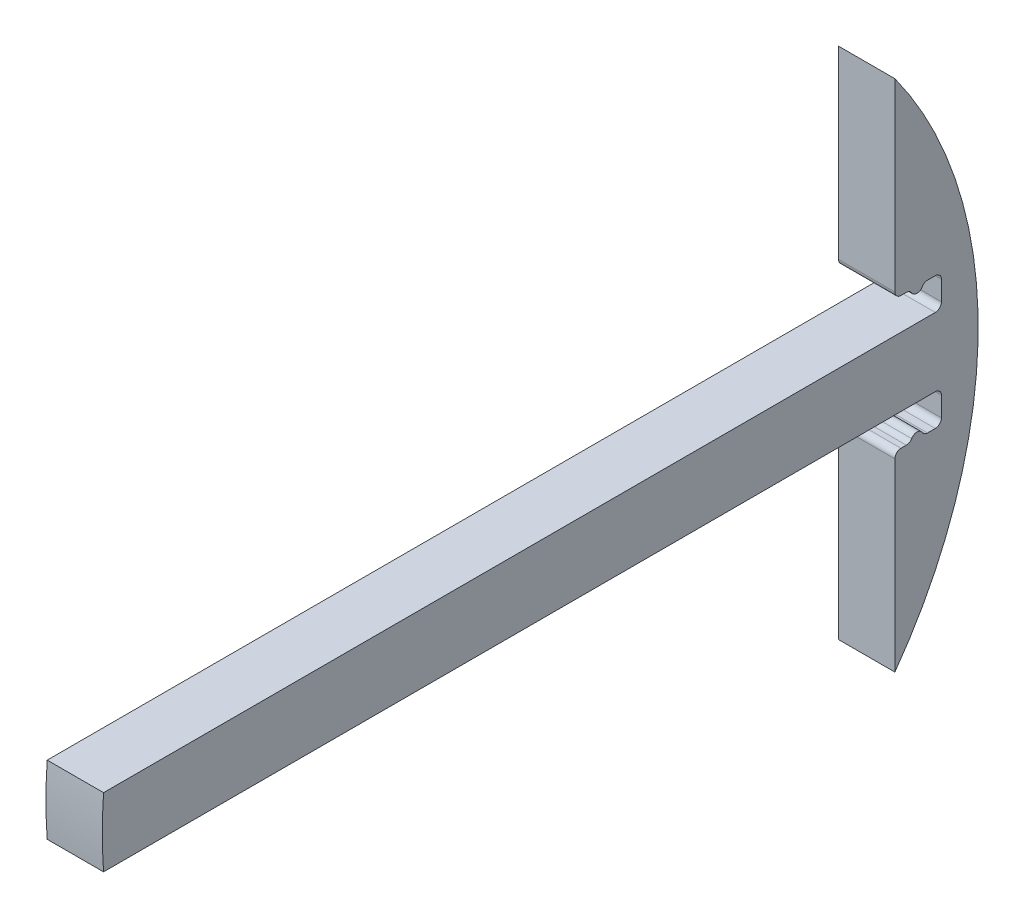
SolidWorks part; units mm, degrees
ref_plane "前视基准面" through (0, 0, 0) normal (0, 0, 1) x (1, 0, 0)
ref_plane "上视基准面" through (0, 0, 0) normal (0, 1, 0) x (1, 0, 0)
ref_plane "右视基准面" through (0, 0, 0) normal (1, 0, 0) x (0, 0, -1)
other "Configuration Table"
sketch "Sketch1" plane through (0, 0, 0) normal (1, 0, 0) x (0, 0, -1)
  circle A0 centre (0, 0) radius 35.75
  dimension "D1" = 71.5
extrude "Boss-Extrude1" add sketch "Sketch1" along normal blind 4.6
sketch "Sketch2" plane through (4.6, 0, 0) normal (1, 0, 0) x (0, 0, -1)
  line L0 (0, 0) -> (35.75, 0)
  line L1 (35.75, 0) -> (35.75, 2.8)
  line L2 (35.75, 2.8) -> (-42.7435, 2.8)
  line L3 (-42.7435, 2.8) -> (-42.7435, -2.8)
  line L4 (-42.7435, -2.8) -> (35.75, -2.8)
  line L5 (35.75, -2.8) -> (35.75, 0)
  line L6 (35.6402, 2.8) -> (32.75, 2.8)
  line L7 (32.75, 2.8) -> (32.75, 5.4)
  line L8 (32.75, 5.4) -> (28.95, 5.4)
  line L9 (28.95, 5.4) -> (28.95, 29.2614)
  line L10 (28.95, 29.2614) -> (35.6402, 29.2614)
  line L11 (35.6402, 29.2614) -> (35.75, 2.8)
  line L12 (35.75, -2.8) -> (-42.7435, -2.8)
  line L13 (32.75, -2.8) -> (32.75, -5.4)
  line L14 (32.75, -5.4) -> (28.95, -5.4)
  line L15 (35.6402, -29.2614) -> (35.75, -2.8)
  line L16 (28.95, -5.4) -> (28.95, -29.2614)
  line L17 (28.95, 5.4) -> (28.95, 2.8)
  line L18 (28.95, -5.4) -> (28.95, -2.8)
  circle A0 centre (0, 0) radius 35.75 construction
  circle A1 centre (0, 0) radius 35.75
  circle A2 centre (30.75, 5.4) radius 0.5
  circle A3 centre (30.75, -5.4) radius 0.5
  circle M6 centre (0, 0) radius 35.75
  dimension "D6" = 2
  dimension "D2" = 1
  dimension "D1" = 2.8
  dimension "D3" = 3
  dimension "D4" = 3.8
  dimension "D5" = 2.6
extrude "Cut-Extrude1" cut sketch "Sketch2" against normal through all contours L17 L9 L2 M6 | L16 L18 L4 M6 | A2 L8 L17 L2 L7 | L14 A3 L13 L12 L18
fillet "Fillet1" radius 0.5 6 edges at (2.3, -5.4, -28.95) (2.3, -2.8, -32.75) (2.3, -5.4, -32.75) (2.3, 2.8, -32.75) (2.3, 5.4, -32.75) (2.3, 5.4, -28.95)
fillet "Fillet2" radius 0.5 4 edges at (2.3, -5.4, -31.25) (2.3, -5.4, -30.25) (2.3, 5.4, -30.25) (2.3, 5.4, -31.25)
